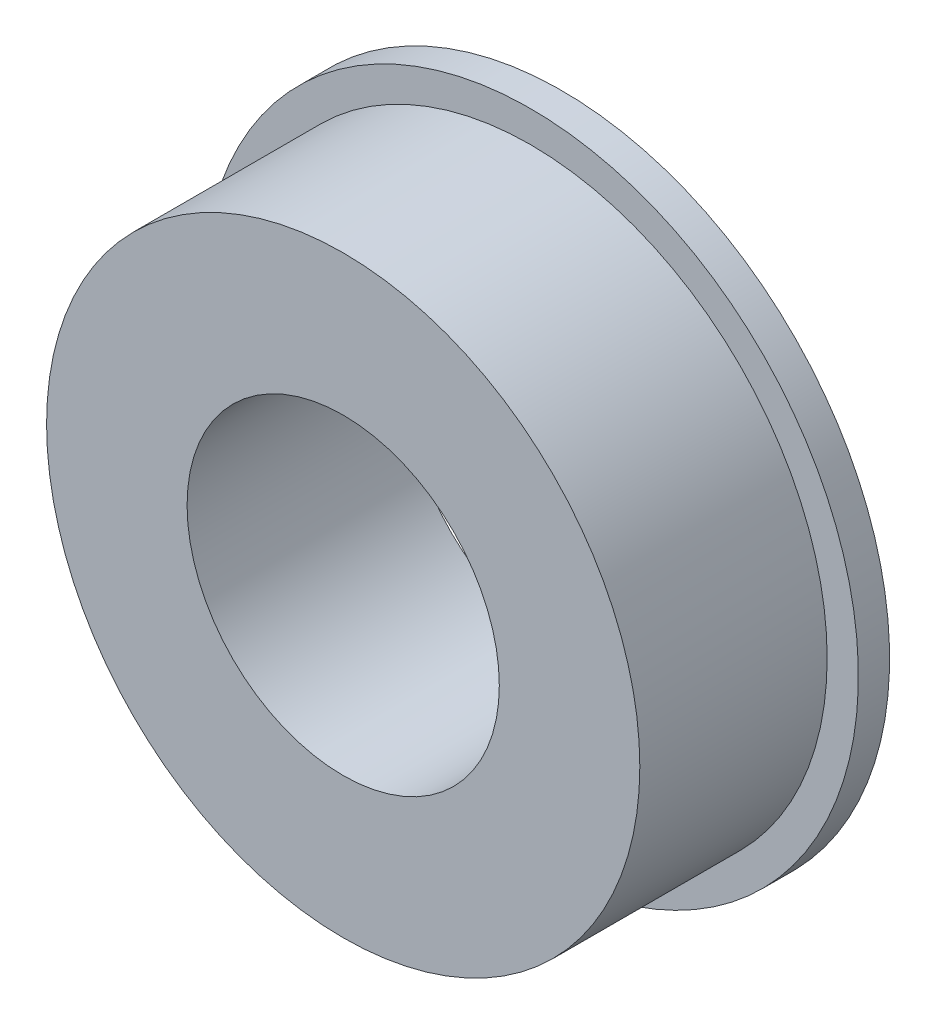
SolidWorks part; units mm, degrees
ref_plane "前视基准面" through (0, 0, 0) normal (0, 0, 1) x (1, 0, 0)
ref_plane "上视基准面" through (0, 0, 0) normal (0, 1, 0) x (1, 0, 0)
ref_plane "右视基准面" through (0, 0, 0) normal (1, 0, 0) x (0, 0, -1)
sketch "草图1" plane through (0, 0, 0) normal (0, 0, 1) x (1, 0, 0)
  circle A0 centre (0, 0) radius 5
  circle A1 centre (0, 0) radius 9.5
  dimension "D1" = 10
  dimension "D2" = 19
extrude "凸台-拉伸1" add sketch "草图1" along normal blind 7
sketch "草图2" plane through (0, 0, 0) normal (0, 0, -1) x (-1, 0, 0)
  circle A0 centre (0, 0) radius 9.5
  circle A1 centre (0, 0) radius 10.5
extrude "凸台-拉伸2" add sketch "草图2" against normal blind 1
